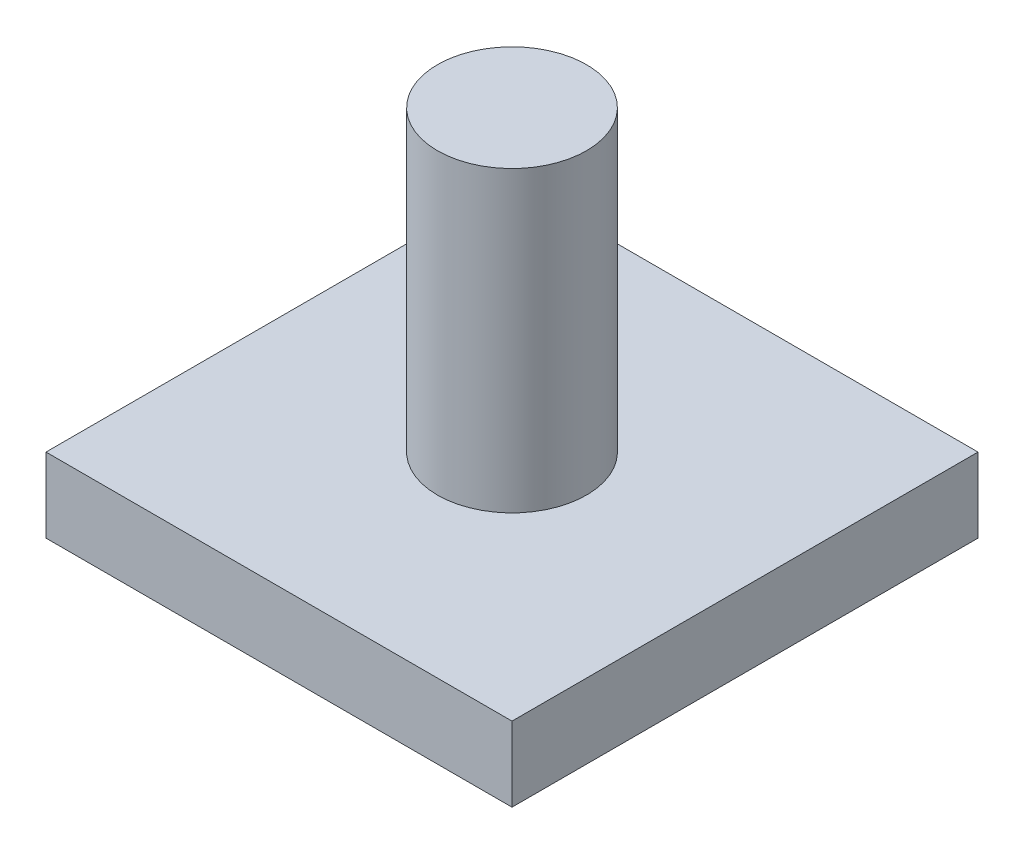
SolidWorks part; units mm, degrees
ref_plane "前视基准面" through (0, 0, 0) normal (0, 0, 1) x (1, 0, 0)
ref_plane "上视基准面" through (0, 0, 0) normal (0, 1, 0) x (1, 0, 0)
ref_plane "右视基准面" through (0, 0, 0) normal (1, 0, 0) x (0, 0, -1)
sketch "草图1" plane through (0, 0, 0) normal (0, 1, 0) x (1, 0, 0)
  line L1 (-6.25, 6.25) -> (6.25, 6.25)
  line L2 (-6.25, 6.25) -> (-6.25, -6.25)
  line L3 (-6.25, -6.25) -> (6.25, -6.25)
  line L4 (6.25, 6.25) -> (6.25, -6.25)
  line L5 (-6.25, 6.25) -> (6.25, -6.25) construction
  line L6 (-6.25, -6.25) -> (6.25, 6.25) construction
  point P0 (0, 0)
  dimension "D1" = 12.5
  dimension "D2" = 12.5
extrude "凸台-拉伸1" add sketch "草图1" along normal blind 2
sketch "草图2" plane through (0, 2, 0) normal (0, 1, 0) x (1, 0, 0)
  circle A0 centre (0, 0) radius 2
  dimension "D1" = 4
extrude "凸台-拉伸2" add sketch "草图2" along normal blind 8
